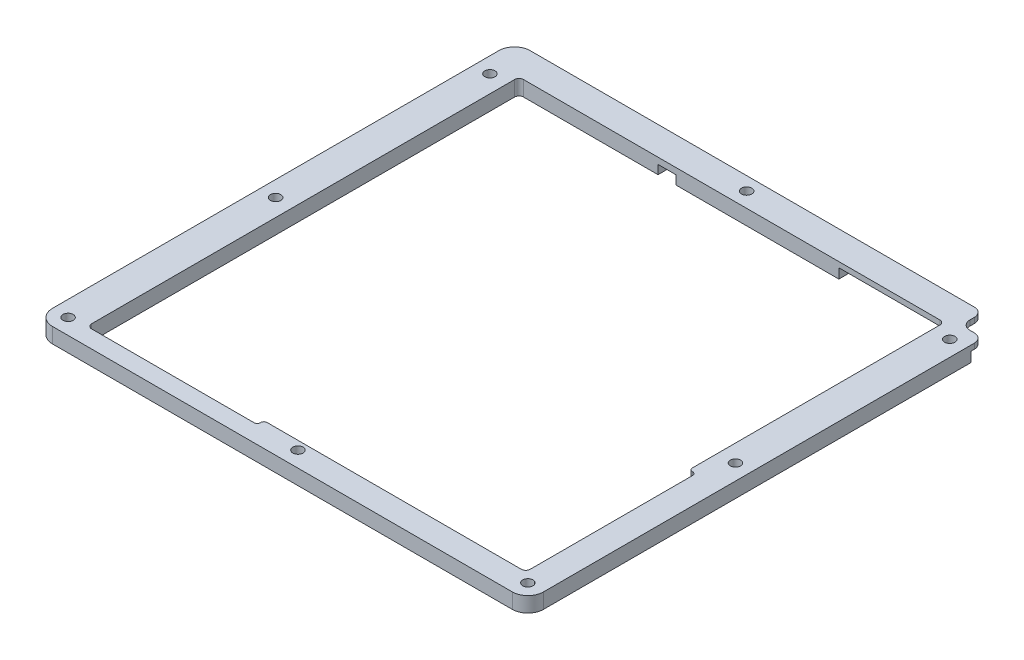
SolidWorks part; units mm, degrees
ref_plane "정면" through (0, 0, 0) normal (0, 0, 1) x (1, 0, 0)
ref_plane "윗면" through (0, 0, 0) normal (0, 1, 0) x (1, 0, 0)
ref_plane "우측면" through (0, 0, 0) normal (1, 0, 0) x (0, 0, -1)
sketch "스케치2" plane through (0, 0, 0) normal (0, 1, 0) x (1, 0, 0)
  line L1 (3.5, 0) -> (106.5, 0)
  line L2 (0, -3.5) -> (0, -104.5)
  line L3 (3.5, -108) -> (106.5, -108)
  line L4 (110, -3.5) -> (110, -104.5)
  circle A0 centre (3.5, -104.5) radius 1.15
  circle A1 centre (106.5, -10) radius 1.15
  circle A2 centre (106.5, -104.5) radius 1.15
  circle A3 centre (55, -104.5) radius 1.15
  circle A4 centre (3.5, -10) radius 1.15
  circle A5 centre (55, -4) radius 1.15
  arc A6 (0, -104.5) -> (3.5, -108) centre (3.5, -104.5) ccw
  arc A7 (106.5, -108) -> (110, -104.5) centre (106.5, -104.5) ccw
  arc A8 (106.5, 0) -> (110, -3.5) centre (106.5, -3.5) cw
  arc A9 (3.5, 0) -> (0, -3.5) centre (3.5, -3.5) ccw
  point P19 (0, -108)
  point P24 (110, 0)
  point P27 (0, 0)
  dimension "D3" = 2.3
  dimension "D5" = 2.3
  dimension "D8" = 2.3
  dimension "D10" = 2.3
  dimension "D12" = 2.3
  dimension "D13" = 2.3
  dimension "D15" = 3.5
  dimension "D1" = 110
  dimension "D2" = 108
  dimension "D4" = 3.5
  dimension "D6" = 3.5
  dimension "D7" = 10
  dimension "D9" = 3.5
  dimension "D11" = 55
  dimension "D14" = 4
extrude "보스-돌출1" add sketch "스케치2" along normal blind 3.4
sketch "스케치3" plane through (0, 3.4, 0) normal (0, 1, 0) x (1, 0, 0)
  line L0 (3.5, -108) -> (106.5, -108) construction
  line L1 (7.375, -102.6) -> (102.625, -102.6)
  line L2 (7.375, -102.6) -> (7.375, -8.35)
  line L3 (8.375, -7.35) -> (101.625, -7.35)
  line L4 (102.625, -63.8) -> (102.625, -8.35)
  line L5 (0, -3.5) -> (0, -104.5) construction
  line L7 (26.425, -7.35) -> (26.425, -102.6) construction
  line L8 (45.475, -7.35) -> (45.475, -102.6) construction
  line L9 (46.175, -102.6) -> (64.525, -102.6) construction
  line L10 (64.525, -7.35) -> (64.525, -102.6) construction
  line L11 (83.575, -7.35) -> (83.575, -102.6) construction
  line L12 (7.375, -26.4) -> (102.625, -26.4) construction
  line L13 (7.375, -45.45) -> (102.625, -45.45) construction
  line L14 (7.375, -64.5) -> (102.625, -64.5) construction
  line L15 (7.375, -83.55) -> (102.625, -83.55) construction
  line L16 (7.375, -102.6) -> (45.475, -102.6)
  line L17 (7.375, -102.6) -> (7.375, -103.1006)
  line L18 (8.375, -104.1006) -> (44.775, -104.1006)
  line L19 (45.475, -103.3) -> (45.475, -103.4006)
  line L20 (102.625, -102.6) -> (103.125, -102.6)
  line L21 (102.625, -102.6) -> (102.625, -64.5)
  line L22 (103.325, -64.5) -> (103.425, -64.5)
  line L23 (104.125, -101.6) -> (104.125, -65.2)
  arc A0 (7.375, -8.35) -> (8.375, -7.35) centre (8.375, -8.35) cw
  arc A1 (101.625, -7.35) -> (102.625, -8.35) centre (101.625, -8.35) cw
  arc A2 (103.125, -102.6) -> (104.125, -101.6) centre (103.125, -101.6) ccw
  arc A3 (7.375, -103.1006) -> (8.375, -104.1006) centre (8.375, -103.1006) ccw
  arc A4 (103.325, -64.5) -> (102.625, -63.8) centre (103.325, -63.8) cw
  arc A5 (103.425, -64.5) -> (104.125, -65.2) centre (103.425, -65.2) cw
  arc A6 (45.475, -103.3) -> (46.175, -102.6) centre (46.175, -103.3) cw
  arc A7 (44.775, -104.1006) -> (45.475, -103.4006) centre (44.775, -103.4006) ccw
  point P30 (7.375, -7.35)
  point P33 (102.625, -7.35)
  dimension "D16" = 1
  dimension "D15" = 0.7
  dimension "D1" = 95.25
  dimension "D2" = 95.25
  dimension "D3" = 5.4
  dimension "D4" = 7.375
  dimension "D5" = 19.05
  dimension "D6" = 19.05
  dimension "D7" = 19.05
  dimension "D8" = 19.05
  dimension "D9" = 19.05
  dimension "D10" = 19.05
  dimension "D11" = 19.05
  dimension "D12" = 19.05
  dimension "D13" = 19.05
  dimension "D14" = 19.05
extrude "컷-돌출4" cut sketch "스케치3" against normal through all
sketch "스케치5" plane through (0, 0, 0) normal (0, -1, 0) x (1, 0, 0)
  line L0 (106.5, 0) -> (3.5, 0) construction
  line L1 (0, 0) -> (6, 0)
  line L2 (0, 0) -> (0, 6)
  line L3 (0, 6) -> (6, 6)
  line L4 (6, 0) -> (6, 6)
  line L5 (22.5, 2) -> (19.5, 2)
  line L6 (22.5, 2) -> (22.5, 0)
  line L7 (22.5, 0) -> (19.5, 0)
  line L8 (19.5, 2) -> (19.5, 0)
  line L9 (8.375, 7.35) -> (101.625, 7.35) construction
  line L10 (51.5, 0) -> (41, 0)
  line L11 (51.5, 0) -> (51.5, 2.7)
  line L12 (51.5, 2.7) -> (41, 2.7)
  line L13 (41, 0) -> (41, 2.7)
  line L14 (38.5, 7.35) -> (42.5, 7.35)
  line L15 (38.5, 7.35) -> (38.5, 4.85)
  line L16 (38.5, 4.85) -> (42.5, 4.85)
  line L17 (42.5, 7.35) -> (42.5, 4.85)
  line L18 (0, 3.5) -> (0, 104.5) construction
  line L19 (110, 104.5) -> (110, 3.5) construction
  line L20 (57, 2.5) -> (61, 2.5)
  line L21 (57, 2.5) -> (57, 0)
  line L22 (57, 0) -> (61, 0)
  line L23 (61, 2.5) -> (61, 0)
  line L24 (79, 0) -> (82, 0)
  line L25 (79, 0) -> (79, 2)
  line L26 (79, 2) -> (82, 2)
  line L27 (82, 0) -> (82, 2)
  line L28 (97, 7.35) -> (103, 7.35)
  line L29 (97, 7.35) -> (97, 2.85)
  line L30 (97, 2.85) -> (103, 2.85)
  line L31 (103, 7.35) -> (103, 2.85)
  line L32 (97, 7.35) -> (95.0201, 7.35)
  line L33 (103, 7.35) -> (97, 7.35)
  line L34 (103, 7.35) -> (103, 8.6367)
  line L35 (103, 8.6367) -> (97, 8.6367)
  line L36 (97, 7.35) -> (97, 8.6367)
  line L37 (102.625, 63.8) -> (102.625, 8.35) construction
  line L38 (103, 7.35) -> (102.625, 7.35)
  line L39 (103, 7.35) -> (103, 8.6367)
  line L40 (103, 8.6367) -> (102.625, 8.6367)
  line L41 (102.625, 7.35) -> (102.625, 8.6367)
  line M33 (0, 104.5) -> (0, 3.5)
  arc M34 (0, 3.5) -> (3.5, 0) centre (3.5, 3.5) ccw
  line M35 (3.5, 0) -> (106.5, 0)
  line M43 (102.625, 63.8) -> (102.625, 8.35)
  arc M44 (102.625, 8.35) -> (101.625, 7.35) centre (101.625, 8.35) cw
  line M45 (101.625, 7.35) -> (8.375, 7.35)
  dimension "D1" = 6
  dimension "D2" = 6
  dimension "D3" = 19.5
  dimension "D4" = 3
  dimension "D5" = 2
  dimension "D6" = 2.7
  dimension "D7" = 10.5
  dimension "D8" = 41
  dimension "D9" = 4
  dimension "D10" = 2.5
  dimension "D11" = 38.5
  dimension "D12" = 5.5
  dimension "D13" = 4
  dimension "D14" = 2.5
  dimension "D15" = 18
  dimension "D16" = 3
  dimension "D17" = 2
  dimension "D18" = 7
  dimension "D19" = 4.5
  dimension "D20" = 6
extrude "컷-돌출8" cut sketch "스케치5" against normal blind 2 contours L31 L33 L28 L29 L30 M45 | L36 L35 M45 M44 M43 | L4 L3 M35 M33 M34 | L13 L11 L12 M35 | L17 L15 L16 M45 | L5 L8 L6 M35 | L23 L20 L21 M35 | L27 L26 L25 M35
sketch "스케치6" plane through (0, 0, 0) normal (0, -1, 0) x (1, 0, 0)
  line L1 (103, 7.35) -> (102.625, 7.35)
  line L2 (103, 7.35) -> (103, 8.35)
  line L3 (103, 8.35) -> (102.625, 8.35)
  line L4 (102.625, 7.35) -> (102.625, 8.35)
  line L5 (102.625, 8.35) -> (101.625, 8.35)
  line L6 (102.625, 8.35) -> (102.625, 7.35)
  line L7 (102.625, 7.35) -> (101.625, 7.35)
  line L8 (101.625, 8.35) -> (101.625, 7.35)
extrude "컷-돌출9" cut sketch "스케치6" against normal blind 2 contours L5 L8 L7 L4
sketch "스케치7" plane through (0, 2, 0) normal (0, -1, 0) x (1, 0, 0)
  line L1 (102.625, 7.35) -> (103, 7.35)
  line L2 (102.625, 7.35) -> (102.625, 2.85)
  line L3 (102.625, 2.85) -> (103, 2.85)
  line L4 (103, 7.35) -> (103, 2.85)
extrude "보스-돌출2" add sketch "스케치7" along normal blind 2
sketch "스케치8" plane through (0, 0, 0) normal (0, 0, -1) x (-1, 0, 0)
  line L1 (-110, 3.4) -> (0, 3.4)
  line L2 (-110, 3.4) -> (-110, 0)
  line L3 (-110, 0) -> (0, 0)
  line L4 (0, 3.4) -> (0, 0)
extrude "컷-돌출10" cut sketch "스케치8" against normal blind 1
sketch "스케치9" plane through (0, 0, 0) normal (0, -1, 0) x (1, 0, 0)
  line L0 (1.0505, 1) -> (6, 1) construction
  line L1 (0, 3.5) -> (6, 3.5)
  line L2 (0, 3.5) -> (0, 1)
  line L3 (0, 1) -> (6, 1)
  line L4 (6, 3.5) -> (6, 1)
  line L5 (108.9495, 1) -> (82, 1) construction
  line L6 (110, 3.5) -> (103.3784, 3.5)
  line L7 (110, 3.5) -> (110, 1)
  line L8 (110, 1) -> (103.3784, 1)
  line L9 (103.3784, 3.5) -> (103.3784, 1)
extrude "보스-돌출3" add sketch "스케치9" against normal through all
fillet "필렛1" radius 3.5 2 edges at (0, 1.7, 1) (110, 1.7, 1)
sketch "스케치10" plane through (0, 0, 0) normal (0, -1, 0) x (1, 0, 0)
  line L0 (110, 1) -> (105, 1)
  line L1 (110, 1) -> (104.8398, 1)
  line L2 (110, 1) -> (110, 6.1991)
  line L3 (110, 6.1991) -> (104.8398, 6.1991)
  line L4 (104.8398, 1) -> (104.8398, 6.1991)
  line L5 (110, 1) -> (110, 6)
  line L6 (110, 6) -> (105, 6)
  line L7 (105, 6) -> (105, 1)
  dimension "D1" = 5.1602
  dimension "D2" = 5
  dimension "D3" = 5
extrude "컷-돌출11" cut sketch "스케치10" against normal through all contours L6 L7 L0 L2
fillet "필렛4" radius 2 2 edges at (105, 1.7, 1) (110, 1.7, 6)
fillet "필렛5" radius 2 1 edges at (105, 1.7, 6)
sketch "스케치11" plane through (0, 3.4, 0) normal (0, 1, 0) x (1, 0, 0)
  line L0 (3.5, -108) -> (106.5, -108) construction
  line L1 (110, -104.5) -> (110, -8) construction
  circle A0 centre (3.5, -58) radius 1.15
  circle A1 centre (106.5, -58) radius 1.15
  dimension "D1" = 2.3
  dimension "D3" = 2.3
  dimension "D2" = 50
  dimension "D4" = 3.5
extrude "컷-돌출12" cut sketch "스케치11" against normal blind 11
sketch "스케치12" plane through (0, 0, 0) normal (0, -1, 0) x (1, 0, 0)
  line L0 (102.625, 63.8) -> (102.625, 2.85) construction
  line L1 (79, 1) -> (102.625, 1)
  line L2 (79, 1) -> (79, 8.35)
  line L3 (79, 8.35) -> (102.625, 8.35)
  line L4 (102.625, 1) -> (102.625, 8.35)
  line L5 (102.625, 2.85) -> (102.625, 8.35) construction
  arc A0 (101.625, 7.35) -> (102.625, 8.35) centre (101.625, 8.35) ccw construction
  point P7 (102.625, 8.35)
extrude "컷-돌출14" cut sketch "스케치12" against normal up to vertex (2 mm away) contours L2 L1 L4 L3
sketch "스케치14" plane through (0, 0, 0) normal (0, -1, 0) x (1, 0, 0)
  line L0 (110, 104.5) -> (110, 8) construction
  line L1 (79, 1) -> (110, 1)
  line L2 (79, 1) -> (79, 13)
  line L3 (79, 13) -> (110, 13)
  line L4 (110, 1) -> (110, 13)
  dimension "D1" = 12
  dimension "D2" = 31
extrude "컷-돌출15" cut sketch "스케치14" against normal blind 2.2
sketch "스케치15" plane through (0, 2.2, 0) normal (0, -1, 0) x (1, 0, 0)
  line L0 (110, 8) -> (110, 13) construction
  line L1 (102.625, 13) -> (110, 13)
  line L2 (102.625, 13) -> (102.625, 8.7)
  line L3 (102.625, 8.7) -> (110, 8.7)
  line L4 (110, 13) -> (110, 8.7)
  circle A0 centre (106.5, 10) radius 1.15
  circle A1 centre (106.5, 10) radius 1.6
  dimension "D1" = 3.2
  dimension "D2" = 4.3
extrude "보스-돌출8" add sketch "스케치15" along normal blind 2.2
equation "\"mm\"=14.7217"
